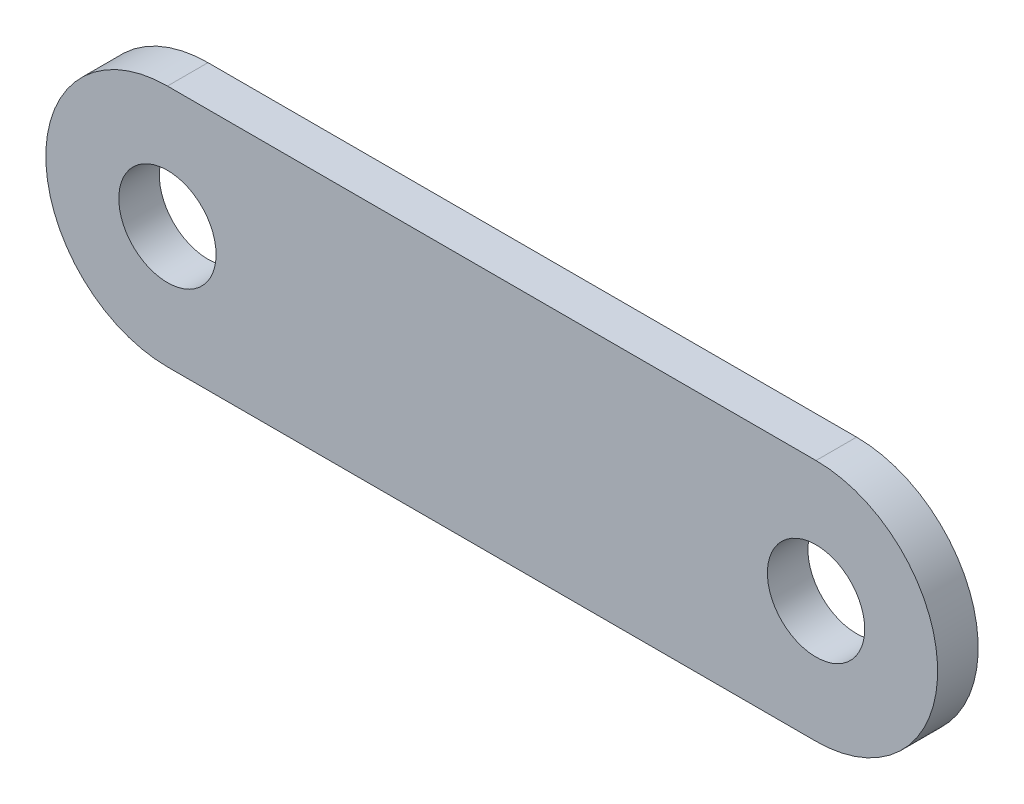
SolidWorks part; units mm, degrees
ref_plane "前视基准面" through (0, 0, 0) normal (0, 0, 1) x (1, 0, 0)
ref_plane "上视基准面" through (0, 0, 0) normal (0, 1, 0) x (1, 0, 0)
ref_plane "右视基准面" through (0, 0, 0) normal (1, 0, 0) x (0, 0, -1)
sketch "草图1" plane through (0, 0, 0) normal (0, 0, 1) x (1, 0, 0)
  line L0 (0, 0) -> (80, 0) construction
  line L1 (0, 15) -> (80, 15)
  line L2 (0, -15) -> (80, -15)
  arc A0 (0, 15) -> (0, -15) centre (0, 0) ccw
  arc A1 (80, -15) -> (80, 15) centre (80, 0) ccw
  circle A2 centre (0, 0) radius 6
  circle A3 centre (80, 0) radius 6
  point P3 (40, 0)
  dimension "D3" = 12
  dimension "D4" = 12
  dimension "D1" = 30
  dimension "D2" = 80
extrude "凸台-拉伸1" add sketch "草图1" along normal mid plane 5
